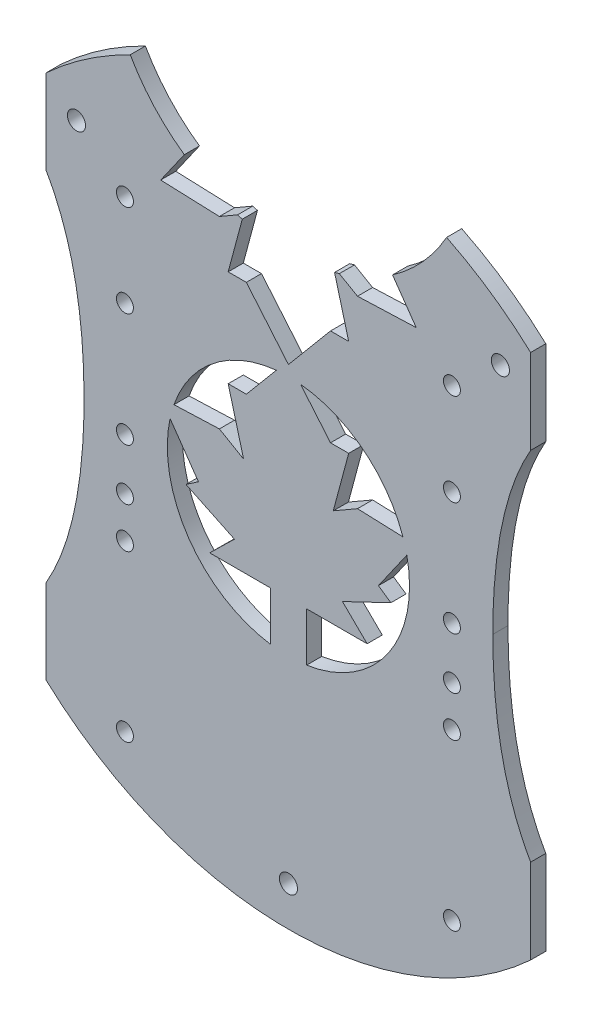
SolidWorks part; units mm, degrees
ref_plane "Front Plane" through (0, 0, 0) normal (0, 0, 1) x (1, 0, 0)
ref_plane "Top Plane" through (0, 0, 0) normal (0, 1, 0) x (1, 0, 0)
ref_plane "Right Plane" through (0, 0, 0) normal (1, 0, 0) x (0, 0, -1)
sketch "Sketch1" plane through (0, 0, 0) normal (0, 0, 1) x (1, 0, 0)
  line L0 (0, 47.9049) -> (0, -75) construction
  line L1 (-50.8, 55.1757) -> (-50.8, -55.1757)
  line L2 (50.8, 55.1757) -> (50.8, -55.1757)
  arc A0 (-33.1727, 67.265) -> (-50.8, 55.1757) centre (0, 0) ccw
  arc A1 (-33.1727, 67.265) -> (33.1727, 67.265) centre (0, 86.0049) ccw
  circle A2 centre (0, -66.675) radius 1.8987
  circle A3 centre (-44.45, 49.6966) radius 1.8987
  circle A4 centre (44.45, 49.6966) radius 1.8986
  arc A5 (-50.8, -55.1757) -> (50.8, -55.1757) centre (0, 0) ccw
  arc A6 (50.8, 55.1757) -> (33.1727, 67.265) centre (0, 0) ccw
  circle A7 centre (0, 0) radius 66.675 construction
  dimension "D8" = 3.7973
  dimension "D11" = 3.7973
  dimension "D5" = 150
  dimension "D7" = 133.35
  dimension "D2" = 66.3453
  dimension "D3" = 38.1
  dimension "D4" = 44.45
  dimension "D6" = 50.8
extrude "Boss-Extrude3" add sketch "Sketch1" along normal blind 3.175
sketch "Sketch3" plane through (0, 0, 3.175) normal (0, 0, 1) x (1, 0, 0)
  line L0 (0, 47.9049) -> (0, -75) construction
  line L1 (0, 25.4) -> (0, -25.4) construction
  line L2 (8.8271, 17.78) -> (2.54, 25.2727)
  line L3 (8.8271, 17.78) -> (12.6371, 17.78)
  line L4 (12.6371, 17.78) -> (9.4043, 5.715)
  line L5 (9.4043, 5.715) -> (14.4843, 8.6479)
  line L6 (14.4843, 8.6479) -> (24.0093, 8.2894)
  line L7 (18.8681, -3.1406) -> (24.8262, 5.3684)
  line L8 (18.8681, -3.1406) -> (21.4871, -4.9356)
  line L9 (21.4871, -4.9356) -> (11.3271, -9.7979)
  line L10 (11.3271, -9.7979) -> (16.51, -14.8779)
  line L11 (16.51, -14.8779) -> (3.81, -14.8779)
  line L12 (3.81, -14.8779) -> (3.81, -25.1126)
  line L13 (-3.81, -14.8779) -> (-3.81, -25.1126)
  line L14 (-16.51, -14.8779) -> (-3.81, -14.8779)
  line L15 (-11.3271, -9.7979) -> (-16.51, -14.8779)
  line L16 (-21.4871, -4.9356) -> (-11.3271, -9.7979)
  line L17 (-18.8681, -3.1406) -> (-21.4871, -4.9356)
  line L18 (-18.8681, -3.1406) -> (-24.8262, 5.3684)
  line L19 (-14.4843, 8.6479) -> (-24.0093, 8.2894)
  line L20 (-9.4043, 5.715) -> (-14.4843, 8.6479)
  line L21 (-12.6371, 17.78) -> (-9.4043, 5.715)
  line L22 (-8.8271, 17.78) -> (-12.6371, 17.78)
  line L23 (-8.8271, 17.78) -> (-2.54, 25.2727)
  arc A0 (-33.1727, 67.265) -> (33.1727, 67.265) centre (0, 86.0049) ccw construction
  arc A1 (-50.8, -55.1757) -> (50.8, -55.1757) centre (0, 0) ccw construction
  arc A2 (3.81, -25.1126) -> (24.8262, 5.3684) centre (0, 0) ccw
  arc A3 (-24.8262, 5.3684) -> (-3.81, -25.1126) centre (0, 0) ccw
  arc A4 (-2.54, 25.2727) -> (-24.0093, 8.2894) centre (0, 0) ccw
  arc A5 (24.0093, 8.2894) -> (2.54, 25.2727) centre (0, 0) ccw
  circle A6 centre (0, 0) radius 25.4 construction
  dimension "D1" = 7.62
  dimension "D2" = 3.81
  dimension "D3" = 12.065
  dimension "D4" = 75
  dimension "D5" = 5.08
  dimension "D6" = 45
  dimension "D7" = 9.525
  dimension "D8" = 3.175
  dimension "D9" = 10.16
  dimension "D10" = 60
  dimension "D11" = 5.08
  dimension "D12" = 12.7
  dimension "D13" = 70
  dimension "D14" = 3.81
  dimension "D15" = 2.921
  dimension "D16" = 35
  dimension "D17" = 40
extrude "Cut-Extrude2" cut sketch "Sketch3" against normal up to surface (3.175 mm away) up to face at (1.8987, -66.675, 0)
sketch "Sketch4" plane through (0, 0, 3.175) normal (0, 0, 1) x (1, 0, 0)
  line L0 (0, 47.9049) -> (0, -75) construction
  line L1 (-38.1, 44.7299) -> (38.1, 44.7299) construction
  line L2 (-38.1, 44.7299) -> (-38.1, -6.0701) construction
  line L3 (-38.1, -6.0701) -> (38.1, -6.0701) construction
  line L4 (38.1, 44.7299) -> (38.1, -6.0701) construction
  line L5 (0, 44.7299) -> (0, -6.0701) construction
  line L6 (-38.1, 19.3299) -> (38.1, 19.3299) construction
  line L7 (-38.1, -9.2451) -> (38.1, -9.2451) construction
  line L8 (-38.1, -9.2451) -> (-38.1, -60.0451) construction
  line L9 (-38.1, -60.0451) -> (38.1, -60.0451) construction
  line L10 (38.1, -9.2451) -> (38.1, -60.0451) construction
  line L11 (0, -9.2451) -> (0, -60.0451) construction
  line L12 (-38.1, -34.6451) -> (38.1, -34.6451) construction
  arc A0 (-33.1727, 67.265) -> (33.1727, 67.265) centre (0, 86.0049) ccw construction
  arc A1 (-50.8, -55.1757) -> (50.8, -55.1757) centre (0, 0) ccw construction
  circle A2 centre (-34.29, 40.9199) radius 1.778
  circle A3 centre (34.29, 40.9199) radius 1.778
  circle A4 centre (34.29, -2.2601) radius 1.778
  circle A5 centre (-34.29, -2.2601) radius 1.778
  circle A6 centre (-34.29, -13.0551) radius 1.778
  circle A7 centre (34.29, -13.0551) radius 1.778
  circle A8 centre (34.29, -56.2351) radius 1.778
  circle A9 centre (-34.29, -56.2351) radius 1.778
  dimension "D3" = 3.556
  dimension "D5" = 3.81
  dimension "D6" = 3.81
  dimension "D7" = 3.556
  dimension "D1" = 76.2
  dimension "D2" = 50.8
  dimension "D4" = 3.175
  dimension "D8" = 3.81
  dimension "D9" = 3.81
  dimension "D10" = 3.175
  dimension "D11" = 50.8
extrude "Cut-Extrude3" cut sketch "Sketch4" against normal up to surface (3.175 mm away) up to face at (-12.3976, 14.4374, 0)
sketch "Sketch5" plane through (0, 0, 3.175) normal (0, 0, 1) x (1, 0, 0)
  line L0 (-38.1, 25.4) -> (38.1, 25.4) construction
  line L1 (-38.1, 25.4) -> (-38.1, -25.4) construction
  line L2 (-38.1, -25.4) -> (38.1, -25.4) construction
  line L3 (38.1, 25.4) -> (38.1, -25.4) construction
  line L4 (0, 25.4) -> (0, -25.4) construction
  line L5 (-38.1, 0) -> (38.1, 0) construction
  line L6 (0, 47.9049) -> (0, -75) construction
  line L7 (-50.8, 0) -> (50.8, 0) construction
  line L8 (-50.8, 55.1757) -> (-50.8, -55.1757) construction
  line L9 (50.8, -55.1757) -> (50.8, 55.1757) construction
  circle A0 centre (-34.29, 21.59) radius 1.778
  circle A1 centre (34.29, 21.59) radius 1.778
  circle A2 centre (34.29, -21.59) radius 1.778
  circle A3 centre (-34.29, -21.59) radius 1.778
  arc A4 (-33.1727, 67.265) -> (33.1727, 67.265) centre (0, 86.0049) ccw construction
  arc A5 (-50.8, -55.1757) -> (50.8, -55.1757) centre (0, 0) ccw construction
  dimension "D1" = 3.556
  dimension "D2" = 3.81
  dimension "D3" = 3.81
  dimension "D4" = 76.2
  dimension "D5" = 50.8
extrude "Cut-Extrude4" cut sketch "Sketch5" against normal up to surface (3.175 mm away) up to face at (-32.512, -56.2351, 0)
sketch "Sketch6" plane through (0, 0, 3.175) normal (0, 0, 1) x (1, 0, 0)
  line L0 (0, 47.9049) -> (0, -75) construction
  line L1 (0, 30.48) -> (0, 81.28) construction
  line L2 (-8.8271, 38.1) -> (-2.54, 30.6073)
  line L3 (-8.8271, 38.1) -> (-12.6371, 38.1)
  line L4 (-12.6371, 38.1) -> (-9.4043, 50.165)
  line L5 (-9.4043, 50.165) -> (-14.4843, 47.2321)
  line L6 (-14.4843, 47.2321) -> (-24.0093, 47.5906)
  line L7 (-18.8681, 59.0206) -> (-24.8262, 50.5116)
  line L8 (-18.8681, 59.0206) -> (-21.4871, 60.8156) construction
  line L9 (-21.4871, 60.8156) -> (-11.3271, 65.6779) construction
  line L10 (-11.3271, 65.6779) -> (-16.51, 70.7579) construction
  line L11 (-16.51, 70.7579) -> (-3.81, 70.7579) construction
  line L12 (-3.81, 70.7579) -> (-3.81, 80.9926) construction
  line L13 (3.81, 70.7579) -> (3.81, 80.9926) construction
  line L14 (16.51, 70.7579) -> (3.81, 70.7579) construction
  line L15 (11.3271, 65.6779) -> (16.51, 70.7579) construction
  line L16 (21.4871, 60.8156) -> (11.3271, 65.6779) construction
  line L17 (18.8681, 59.0206) -> (21.4871, 60.8156) construction
  line L18 (18.8681, 59.0206) -> (24.8262, 50.5116)
  line L19 (14.4843, 47.2321) -> (24.0093, 47.5906)
  line L20 (9.4043, 50.165) -> (14.4843, 47.2321)
  line L21 (12.6371, 38.1) -> (9.4043, 50.165)
  line L22 (8.8271, 38.1) -> (12.6371, 38.1)
  line L23 (8.8271, 38.1) -> (2.54, 30.6073)
  line L24 (0, 27.5803) -> (-2.54, 30.6073)
  line L25 (0, 27.5803) -> (2.54, 30.6073)
  line L26 (24.8262, 50.5116) -> (26.798, 47.6956)
  line L27 (26.798, 47.6956) -> (24.0093, 47.5906)
  line L28 (-24.0093, 47.5906) -> (-26.798, 47.6956)
  line L29 (-26.798, 47.6956) -> (-24.8262, 50.5116)
  line L30 (-3.81, 80.9926) -> (3.81, 80.9926) construction
  line L31 (-25.2051, 59.0206) -> (25.2051, 59.0206) construction
  line L32 (-18.8681, 59.0206) -> (18.8681, 59.0206)
  arc A0 (-33.1727, 67.265) -> (33.1727, 67.265) centre (0, 86.0049) ccw construction
  arc A1 (-50.8, -55.1757) -> (50.8, -55.1757) centre (0, 0) ccw construction
  circle A6 centre (0, 55.88) radius 25.4 construction
  dimension "D19" = 55.88
  dimension "D18" = 50.8
  dimension "D1" = 7.62
  dimension "D2" = 3.81
  dimension "D3" = 12.065
  dimension "D4" = 75
  dimension "D5" = 5.08
  dimension "D6" = 45
  dimension "D7" = 9.525
  dimension "D8" = 3.175
  dimension "D9" = 10.16
  dimension "D10" = 60
  dimension "D11" = 5.08
  dimension "D12" = 12.7
  dimension "D13" = 70
  dimension "D14" = 3.81
  dimension "D15" = 2.921
  dimension "D16" = 35
  dimension "D17" = 40
  dimension "D20" = 2.7887
  dimension "D21" = 2.816
  dimension "D22" = 21.972
extrude "Cut-Extrude5" cut sketch "Sketch6" against normal up to surface (3.175 mm away) up to face at (-32.512, -21.59, 0)
sketch "Sketch7" plane through (0, 0, 3.175) normal (0, 0, 1) x (1, 0, 0)
  line L0 (0, 27.5803) -> (0, -75) construction
  line L1 (-50.8, 0) -> (50.8, 0) construction
  line L2 (-50.8, 55.1757) -> (-50.8, -55.1757) construction
  line L3 (50.8, -55.1757) -> (50.8, 55.1757) construction
  line L4 (-50.8, 37.3957) -> (-50.8, -37.3957)
  line L5 (-34.9178, 9.887) -> (-66.6678, 64.8796) construction
  line L6 (50.8, 37.3957) -> (50.8, -37.3957)
  arc A0 (-50.8, -55.1757) -> (50.8, -55.1757) centre (0, 0) ccw construction
  spline S0 degree 2 poles (-50.8, 37.3957) (-42.8625, 23.6476) (-42.8625, 0) knots 0 0 0 1 1 1
  spline S1 degree 2 poles (-50.8, -37.3957) (-42.8625, -23.6476) (-42.8625, 0) knots 0 0 0 1 1 1
  spline S2 degree 2 poles (50.8, -37.3957) (42.8625, -23.6476) (42.8625, 0) knots 0 0 0 1 1 1
  spline S3 degree 2 poles (50.8, 37.3957) (42.8625, 23.6476) (42.8625, 0) knots 0 0 0 1 1 1
  dimension "D2" = 31.75
  dimension "D1" = 17.78
  dimension "D3" = 30
extrude "Cut-Extrude6" cut sketch "Sketch7" against normal up to surface (3.175 mm away) up to face at (-32.512, -21.59, 0)
